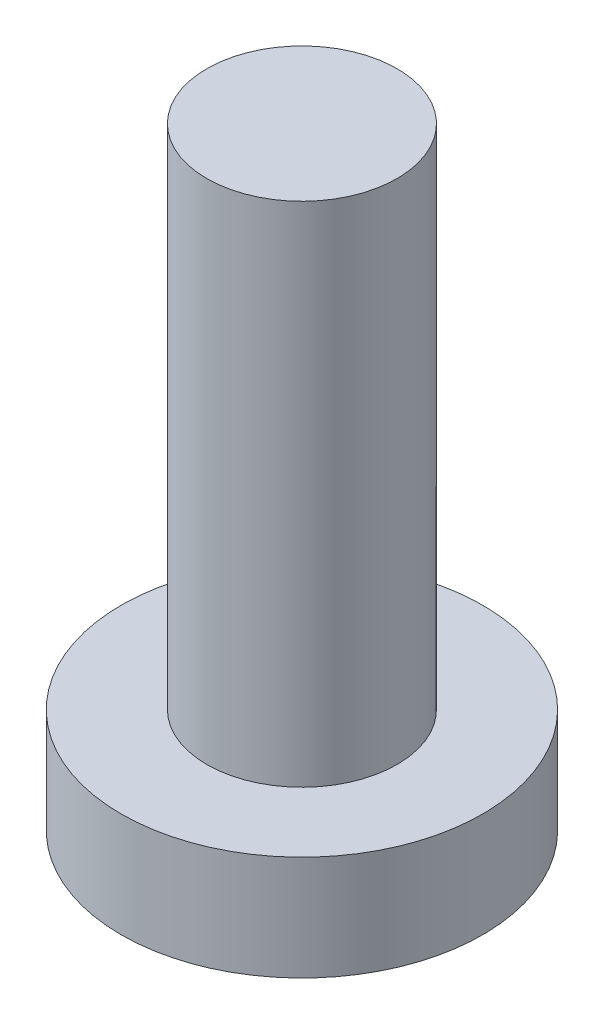
SolidWorks part; units mm, degrees
ref_plane "前视基准面" through (0, 0, 0) normal (0, 0, 1) x (1, 0, 0)
ref_plane "上视基准面" through (0, 0, 0) normal (0, 1, 0) x (1, 0, 0)
ref_plane "右视基准面" through (0, 0, 0) normal (1, 0, 0) x (0, 0, -1)
sketch "草图1" plane through (0, 0, 0) normal (0, 1, 0) x (1, 0, 0)
  circle A0 centre (0, 0) radius 2.85
  dimension "D1" = 5.7
extrude "凸台-拉伸1" add sketch "草图1" along normal blind 1.65
sketch "草图2" plane through (0, 1.65, 0) normal (0, 1, 0) x (1, 0, 0)
  circle A0 centre (0, 0) radius 1.5
  dimension "D1" = 3
extrude "凸台-拉伸2" add sketch "草图2" along normal blind 8
